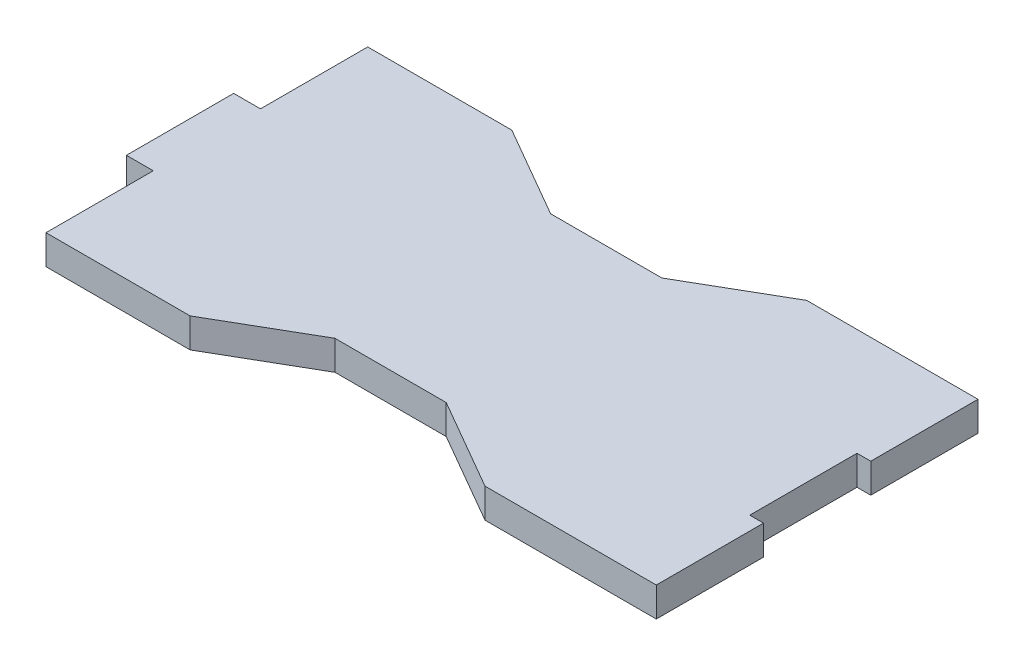
SolidWorks part; units mm, degrees
material "cardboard"
ref_plane "Front Plane" through (0, 0, 0) normal (0, 0, 1) x (1, 0, 0)
ref_plane "Top Plane" through (0, 0, 0) normal (0, 1, 0) x (1, 0, 0)
ref_plane "Right Plane" through (0, 0, 0) normal (1, 0, 0) x (0, 0, -1)
sketch "Sketch1" plane through (0, 0, 0) normal (0, 1, 0) x (1, 0, 0)
  line L0 (77.4818, 11.8659) -> (70.6317, 7.911)
  line L1 (102.9818, -12.1341) -> (109.832, -8.1792)
  line L2 (118.1317, 7.911) -> (109.832, 7.911)
  line L3 (118.1317, -8.1792) -> (109.832, -8.1792)
  line L4 (70.6317, 7.911) -> (62.332, 7.911)
  line L5 (124.9818, 11.8659) -> (118.1317, 7.911)
  line L6 (124.9818, -12.1341) -> (118.1317, -8.1792)
  line L7 (102.9818, 11.8659) -> (109.832, 7.911)
  line L8 (124.9818, 11.8659) -> (137.7318, 11.8659)
  line L9 (124.9818, -12.1341) -> (161.7318, -12.1341)
  line L10 (55.4818, 11.8659) -> (62.332, 7.911)
  line L11 (55.4818, -12.1341) -> (62.332, -8.1792)
  line L12 (77.4818, -12.1341) -> (70.6317, -8.1792)
  line L13 (70.6317, -8.1792) -> (62.332, -8.1792)
  line L14 (77.4818, 11.8659) -> (102.9818, 11.8659)
  line L15 (77.4818, -12.1341) -> (102.9818, -12.1341)
  line L16 (-12.2682, 77.6159) -> (-8.3133, 70.7658)
  line L17 (11.7318, 103.1159) -> (7.7769, 109.966)
  line L18 (-8.3133, 118.2658) -> (-8.3133, 109.966)
  line L19 (7.7769, 118.2658) -> (7.7769, 109.966)
  line L20 (-8.3133, 70.7658) -> (-8.3133, 62.466)
  line L21 (-12.2682, 125.1159) -> (-8.3133, 118.2658)
  line L22 (11.7318, 125.1159) -> (7.7769, 118.2658)
  line L23 (-12.2682, 103.1159) -> (-8.3133, 109.966)
  line L24 (-12.2682, 125.1159) -> (-12.2682, 137.8659)
  line L25 (11.7318, 125.1159) -> (11.7318, 161.8659)
  line L26 (-12.2682, 55.6159) -> (-8.3133, 62.466)
  line L27 (11.7318, 55.6159) -> (7.7769, 62.466)
  line L28 (11.7318, 77.6159) -> (7.7769, 70.7658)
  line L29 (7.7769, 70.7658) -> (7.7769, 62.466)
  line L30 (-12.2682, 77.6159) -> (-12.2682, 103.1159)
  line L31 (11.7318, 77.6159) -> (11.7318, 103.1159)
  line L32 (90.2318, 36.8659) -> (90.2318, 16.8659)
  line L33 (89.2318, 36.8659) -> (89.2318, 30.8659)
  line L34 (36.7318, 11.8659) -> (42.7318, 11.8659)
  line L35 (89.2318, 30.8659) -> (91.2318, 30.8659)
  line L36 (41.4818, 11.8659) -> (41.4818, 9.8659)
  line L37 (42.7318, 11.8659) -> (55.4818, 11.8659)
  line L38 (137.7318, 11.8659) -> (137.7318, -12.1341)
  line L39 (137.7318, 11.8659) -> (161.7318, 11.8659)
  line L40 (161.7318, 11.8659) -> (161.7318, 9.8659)
  line L41 (-28.7646, 14.2202) -> (-0.2682, -14.2762)
  line L42 (-28.7646, 14.2202) -> (-14.6225, 28.3623)
  line L43 (-0.2682, -14.2762) -> (13.8739, -0.1341)
  line L44 (-14.6225, 28.3623) -> (13.8739, -0.1341)
  line L45 (137.7318, 11.8659) -> (137.7318, 36.8659)
  line L46 (39.7318, 36.8659) -> (161.7318, 36.8659)
  line L47 (161.7318, 36.8659) -> (161.7318, 11.8659)
  line L48 (91.2318, 30.8659) -> (91.2318, 22.8659)
  line L49 (137.7318, 36.8659) -> (137.7318, 60.8659)
  line L50 (137.7318, 60.8659) -> (146.7318, 60.8659)
  line L51 (42.7318, 36.8659) -> (42.7318, 16.8659)
  line L52 (161.7318, 60.8659) -> (161.7318, 51.1879)
  line L53 (146.7318, 60.8659) -> (146.7318, 63.0659)
  line L54 (152.7318, 63.0659) -> (152.7318, 60.8659)
  line L55 (152.7318, 60.8659) -> (161.7318, 60.8659)
  line L56 (-59.2682, 137.8659) -> (-59.2682, 113.3659)
  line L57 (-39.2682, 113.3659) -> (-39.2682, 137.8659)
  line L58 (91.2318, 22.8659) -> (89.2318, 22.8659)
  line L59 (137.7318, -12.1341) -> (137.7318, -37.1341)
  line L60 (146.7318, -37.1341) -> (152.7318, -37.1341)
  line L61 (161.7318, -37.1341) -> (161.7318, -12.1341)
  line L62 (42.7318, -37.1341) -> (42.7318, -17.1341)
  line L63 (137.7318, -37.1341) -> (137.7318, -38.3141)
  line L64 (152.7318, -38.3141) -> (161.7318, -38.3141)
  line L65 (161.7318, -38.3141) -> (161.7318, -37.1341)
  line L66 (146.7318, -38.3141) -> (146.7318, -37.1341)
  line L67 (152.7318, -38.3141) -> (152.7318, -37.1341)
  line L68 (-38.4482, -138.1341) -> (-38.4482, -147.1341)
  line L69 (89.2318, 22.8659) -> (89.2318, 16.8659)
  line L70 (89.2318, 11.8659) -> (89.2318, 3.8659)
  line L71 (42.7318, -12.1341) -> (55.4818, -12.1341)
  line L72 (36.7318, -12.1341) -> (42.7318, -12.1341)
  line L73 (90.2056, 11.8659) -> (90.2056, -12.1341)
  line L74 (89.2318, 3.8659) -> (91.2318, 3.8659)
  line L75 (91.2318, 3.8659) -> (91.2318, -4.1341)
  line L76 (91.2318, -4.1341) -> (89.2318, -4.1341)
  line L77 (135.7318, 11.8659) -> (135.7318, 3.8659)
  line L78 (135.7318, 3.8659) -> (139.7318, 3.8659)
  line L79 (37.9118, 161.8659) -> (37.9118, 152.8659)
  line L80 (37.7318, 34.8659) -> (37.7318, 18.8659)
  line L81 (39.7318, 16.8659) -> (137.7318, 16.8659)
  line L82 (41.4818, 23.8659) -> (41.4818, 16.8659)
  line L83 (42.7318, 29.8659) -> (39.7318, 29.8659)
  line L84 (39.7318, 29.8659) -> (39.7318, 23.8659)
  line L85 (43.9818, 5.8659) -> (41.4818, 5.8659)
  line L86 (5.7318, -41.8841) -> (5.7318, -39.8841)
  line L87 (41.4818, -6.1341) -> (43.9818, -6.1341)
  line L88 (43.9818, 5.8659) -> (43.9818, -6.1341)
  line L89 (42.7318, 11.8659) -> (42.7318, 5.8659)
  line L90 (41.4818, 9.8659) -> (43.9818, 9.8659)
  line L91 (43.9818, 9.8659) -> (43.9818, 7.8659)
  line L92 (43.9818, 7.8659) -> (41.4818, 7.8659)
  line L93 (41.4818, 7.8659) -> (41.4818, 5.8659)
  line L94 (41.4818, -8.1341) -> (41.4818, -6.1341)
  line L95 (43.9818, -8.1341) -> (41.4818, -8.1341)
  line L96 (43.9818, -10.1341) -> (43.9818, -8.1341)
  line L97 (41.4818, -10.1341) -> (43.9818, -10.1341)
  line L98 (41.4818, -12.1341) -> (41.4818, -10.1341)
  line L99 (139.7318, 3.8659) -> (139.7318, -4.1341)
  line L100 (139.7318, -4.1341) -> (135.7318, -4.1341)
  line L101 (135.7318, -4.1341) -> (135.7318, -12.1341)
  line L102 (137.7318, 13.8659) -> (145.7318, 13.8659)
  line L103 (145.7318, 13.8659) -> (145.7318, 9.8659)
  line L104 (145.7318, 9.8659) -> (153.7318, 9.8659)
  line L105 (153.7318, 9.8659) -> (153.7318, 13.8659)
  line L106 (153.7318, 13.8659) -> (161.7318, 13.8659)
  line L107 (136.2318, 36.8659) -> (136.2318, 30.8659)
  line L108 (136.2318, 30.8659) -> (139.2318, 30.8659)
  line L109 (139.2318, 30.8659) -> (139.2318, 22.8659)
  line L110 (139.2318, 22.8659) -> (136.2318, 22.8659)
  line L111 (136.2318, 22.8659) -> (136.2318, 16.8659)
  line L112 (89.2318, -4.1341) -> (89.2318, -12.1341)
  line L113 (89.2318, -23.1341) -> (89.2318, -17.1341)
  line L114 (90.2318, -37.1341) -> (90.2318, -17.1341)
  line L115 (91.2318, -23.1341) -> (89.2318, -23.1341)
  line L116 (91.2318, -31.1341) -> (91.2318, -23.1341)
  line L117 (153.7318, -14.1341) -> (161.7318, -14.1341)
  line L118 (153.7318, -10.1341) -> (153.7318, -14.1341)
  line L119 (145.7318, -10.1341) -> (153.7318, -10.1341)
  line L120 (145.7318, -14.1341) -> (145.7318, -10.1341)
  line L121 (137.7318, -14.1341) -> (145.7318, -14.1341)
  line L122 (136.2318, -23.1341) -> (136.2318, -17.1341)
  line L123 (139.2318, -23.1341) -> (136.2318, -23.1341)
  line L124 (41.4818, 36.8659) -> (41.4818, 29.8659)
  line L125 (42.7318, 23.8659) -> (39.7318, 23.8659)
  line L126 (137.7318, -37.1341) -> (39.7318, -37.1341)
  line L127 (37.7318, -35.1341) -> (37.7318, -19.1341)
  line L128 (39.7318, -17.1341) -> (137.7318, -17.1341)
  line L129 (139.2318, -31.1341) -> (139.2318, -23.1341)
  line L130 (136.2318, -31.1341) -> (139.2318, -31.1341)
  line L131 (136.2318, -37.1341) -> (136.2318, -31.1341)
  line L132 (89.2318, -31.1341) -> (91.2318, -31.1341)
  line L133 (89.2318, -37.1341) -> (89.2318, -31.1341)
  line L134 (137.7318, 38.8659) -> (145.7318, 38.8659)
  line L135 (145.7318, 38.8659) -> (145.7318, 34.8659)
  line L136 (145.7318, 34.8659) -> (153.7318, 34.8659)
  line L137 (153.7318, 34.8659) -> (153.7318, 38.8659)
  line L138 (153.7318, 38.8659) -> (161.7318, 38.8659)
  line L139 (-44.7682, 133.6159) -> (-44.7682, 117.6159)
  line L140 (-56.2682, 133.6159) -> (-53.7682, 133.6159)
  line L141 (-56.2682, 133.6159) -> (-56.2682, 117.6159)
  line L142 (-56.2682, 117.6159) -> (-53.7682, 117.6159)
  line L143 (-53.7682, 133.6159) -> (-53.7682, 117.6159)
  line L144 (41.4818, -24.1341) -> (41.4818, -17.1341)
  line L145 (42.7318, -24.1341) -> (39.7318, -24.1341)
  line L146 (39.7318, -30.1341) -> (39.7318, -24.1341)
  line L147 (42.7318, -30.1341) -> (39.7318, -30.1341)
  line L148 (41.4818, -37.1341) -> (41.4818, -30.1341)
  line L149 (196.7318, 4.8659) -> (196.7318, -5.1341)
  line L150 (191.7318, 9.8659) -> (161.7318, 9.8659)
  line L151 (191.7318, -10.1341) -> (161.7318, -10.1341)
  line L152 (191.7318, 9.8659) -> (196.7318, 4.8659)
  line L153 (196.7318, -5.1341) -> (191.7318, -10.1341)
  line L154 (161.7318, -10.1341) -> (161.7318, -12.1341)
  line L155 (137.7318, 63.0659) -> (146.7318, 63.0659)
  line L156 (137.7318, 63.0659) -> (137.7318, 65.0659)
  line L157 (137.7318, 65.0659) -> (161.7318, 65.0659)
  line L158 (161.7318, 65.0659) -> (161.7318, 63.0659)
  line L159 (152.7318, 63.0659) -> (161.7318, 63.0659)
  line L160 (-42.2682, 117.6159) -> (-44.7682, 117.6159)
  line L161 (-42.2682, 133.6159) -> (-42.2682, 117.6159)
  line L162 (-42.2682, 133.6159) -> (-44.7682, 133.6159)
  line L163 (155.1318, 51.1879) -> (161.7318, 51.1879)
  line L164 (155.1318, 51.1879) -> (155.1318, 46.6879)
  line L165 (155.1318, 46.6879) -> (161.7318, 46.6879)
  line L166 (161.7318, 46.6879) -> (161.7318, 36.8659)
  line L167 (11.7318, -77.8841) -> (7.7769, -71.034)
  line L168 (-12.2682, -103.3841) -> (-8.3133, -110.2342)
  line L169 (7.7769, -118.534) -> (7.7769, -110.2342)
  line L170 (11.7318, -37.1341) -> (11.7318, -43.1341)
  line L171 (11.7318, -41.8841) -> (9.7318, -41.8841)
  line L172 (11.7318, -43.1341) -> (11.7318, -55.8841)
  line L173 (-8.3133, -118.534) -> (-8.3133, -110.2342)
  line L174 (7.7769, -71.034) -> (7.7769, -62.7342)
  line L175 (11.7318, -125.3841) -> (7.7769, -118.534)
  line L176 (-12.2682, -125.3841) -> (-8.3133, -118.534)
  line L177 (11.7318, -103.3841) -> (7.7769, -110.2342)
  line L178 (11.7318, -125.3841) -> (11.7318, -138.1341)
  line L179 (-12.2682, -125.3841) -> (-12.2682, -162.1341)
  line L180 (11.7318, -55.8841) -> (7.7769, -62.7342)
  line L181 (-12.2682, -55.8841) -> (-8.3133, -62.7342)
  line L182 (36.7318, -43.1341) -> (16.7318, -43.1341)
  line L183 (-12.2682, -77.8841) -> (-8.3133, -71.034)
  line L184 (-8.3133, -71.034) -> (-8.3133, -62.7342)
  line L185 (11.7318, -77.8841) -> (11.7318, -103.3841)
  line L186 (-12.2682, -77.8841) -> (-12.2682, -103.3841)
  line L187 (36.7318, -90.6341) -> (16.7318, -90.6341)
  line L188 (36.7318, -89.6341) -> (30.7318, -89.6341)
  line L189 (30.7318, -89.6341) -> (30.7318, -91.6341)
  line L190 (11.7318, -138.1341) -> (-12.2682, -138.1341)
  line L191 (11.7318, -138.1341) -> (11.7318, -162.1341)
  line L192 (11.7318, -162.1341) -> (9.7318, -162.1341)
  line L193 (11.7318, -138.1341) -> (36.7318, -138.1341)
  line L194 (36.7318, -40.1341) -> (36.7318, -162.1341)
  line L195 (-37.2682, -43.1341) -> (-17.2682, -43.1341)
  line L196 (36.7318, -162.1341) -> (11.7318, -162.1341)
  line L197 (30.7318, -91.6341) -> (22.7318, -91.6341)
  line L198 (36.7318, -138.1341) -> (60.7318, -138.1341)
  line L199 (60.7318, -138.1341) -> (60.7318, -147.1341)
  line L200 (60.7318, -162.1341) -> (51.0538, -162.1341)
  line L201 (60.7318, -147.1341) -> (62.9318, -147.1341)
  line L202 (62.9318, -153.1341) -> (60.7318, -153.1341)
  line L203 (60.7318, -153.1341) -> (60.7318, -162.1341)
  line L204 (-12.2682, -43.1341) -> (-12.2682, -55.8841)
  line L205 (-12.2682, -37.1341) -> (-12.2682, -43.1341)
  line L206 (22.7318, -91.6341) -> (22.7318, -89.6341)
  line L207 (-12.2682, -138.1341) -> (-37.2682, -138.1341)
  line L208 (-37.2682, -147.1341) -> (-37.2682, -153.1341)
  line L209 (37.9118, 146.8659) -> (37.9118, 137.8659)
  line L210 (34.7318, -38.1341) -> (18.7318, -38.1341)
  line L211 (16.7318, -40.1341) -> (16.7318, -138.1341)
  line L212 (23.7318, -41.8841) -> (16.7318, -41.8841)
  line L213 (29.7318, -43.1341) -> (29.7318, -40.1341)
  line L214 (29.7318, -40.1341) -> (23.7318, -40.1341)
  line L215 (5.7318, -44.3841) -> (5.7318, -41.8841)
  line L216 (-37.2682, -162.1341) -> (-12.2682, -162.1341)
  line L217 (-6.2682, -41.8841) -> (-6.2682, -44.3841)
  line L218 (5.7318, -44.3841) -> (-6.2682, -44.3841)
  line L219 (11.7318, -43.1341) -> (5.7318, -43.1341)
  line L220 (9.7318, -41.8841) -> (9.7318, -44.3841)
  line L221 (9.7318, -44.3841) -> (7.7318, -44.3841)
  line L222 (7.7318, -44.3841) -> (7.7318, -41.8841)
  line L223 (7.7318, -41.8841) -> (5.7318, -41.8841)
  line L224 (-8.2682, -41.8841) -> (-6.2682, -41.8841)
  line L225 (-8.2682, -44.3841) -> (-8.2682, -41.8841)
  line L226 (-10.2682, -44.3841) -> (-8.2682, -44.3841)
  line L227 (-10.2682, -41.8841) -> (-10.2682, -44.3841)
  line L228 (-12.2682, -41.8841) -> (-10.2682, -41.8841)
  line L229 (-37.2682, -138.1341) -> (-38.4482, -138.1341)
  line L230 (-38.4482, -153.1341) -> (-38.4482, -162.1341)
  line L231 (-38.4482, -162.1341) -> (-37.2682, -162.1341)
  line L232 (-38.4482, -147.1341) -> (-37.2682, -147.1341)
  line L233 (-38.4482, -153.1341) -> (-37.2682, -153.1341)
  line L234 (-162.2682, 38.0459) -> (-153.2682, 38.0459)
  line L235 (22.7318, -89.6341) -> (16.7318, -89.6341)
  line L236 (11.7318, -89.6341) -> (3.7318, -89.6341)
  line L237 (11.7318, -90.6079) -> (-12.2682, -90.6079)
  line L238 (3.7318, -89.6341) -> (3.7318, -91.6341)
  line L239 (3.7318, -91.6341) -> (-4.2682, -91.6341)
  line L240 (-4.2682, -91.6341) -> (-4.2682, -89.6341)
  line L241 (11.7318, -136.1341) -> (3.7318, -136.1341)
  line L242 (3.7318, -136.1341) -> (3.7318, -140.1341)
  line L243 (3.7318, -140.1341) -> (-4.2682, -140.1341)
  line L244 (-4.2682, -140.1341) -> (-4.2682, -136.1341)
  line L245 (-4.2682, -136.1341) -> (-12.2682, -136.1341)
  line L246 (13.7318, -138.1341) -> (13.7318, -146.1341)
  line L247 (13.7318, -146.1341) -> (9.7318, -146.1341)
  line L248 (9.7318, -146.1341) -> (9.7318, -154.1341)
  line L249 (9.7318, -154.1341) -> (13.7318, -154.1341)
  line L250 (13.7318, -154.1341) -> (13.7318, -162.1341)
  line L251 (36.7318, -136.6341) -> (30.7318, -136.6341)
  line L252 (30.7318, -136.6341) -> (30.7318, -139.6341)
  line L253 (30.7318, -139.6341) -> (22.7318, -139.6341)
  line L254 (36.7318, -41.8841) -> (29.7318, -41.8841)
  line L255 (23.7318, -43.1341) -> (23.7318, -40.1341)
  line L256 (-37.2682, -138.1341) -> (-37.2682, -40.1341)
  line L257 (-35.2682, -38.1341) -> (-19.2682, -38.1341)
  line L258 (-17.2682, -40.1341) -> (-17.2682, -138.1341)
  line L259 (22.7318, -139.6341) -> (22.7318, -136.6341)
  line L260 (22.7318, -136.6341) -> (16.7318, -136.6341)
  line L261 (-4.2682, -89.6341) -> (-12.2682, -89.6341)
  line L262 (-23.2682, -89.6341) -> (-17.2682, -89.6341)
  line L263 (-37.2682, -90.6341) -> (-17.2682, -90.6341)
  line L264 (-23.2682, -91.6341) -> (-23.2682, -89.6341)
  line L265 (-31.2682, -91.6341) -> (-23.2682, -91.6341)
  line L266 (-14.2682, -154.1341) -> (-14.2682, -162.1341)
  line L267 (-10.2682, -154.1341) -> (-14.2682, -154.1341)
  line L268 (-10.2682, -146.1341) -> (-10.2682, -154.1341)
  line L269 (-14.2682, -146.1341) -> (-10.2682, -146.1341)
  line L270 (-14.2682, -138.1341) -> (-14.2682, -146.1341)
  line L271 (-23.2682, -136.6341) -> (-17.2682, -136.6341)
  line L272 (-23.2682, -139.6341) -> (-23.2682, -136.6341)
  line L273 (-31.2682, -139.6341) -> (-23.2682, -139.6341)
  line L274 (-24.2682, -41.8841) -> (-17.2682, -41.8841)
  line L275 (-24.2682, -43.1341) -> (-24.2682, -40.1341)
  line L276 (-30.2682, -40.1341) -> (-24.2682, -40.1341)
  line L277 (-30.2682, -43.1341) -> (-30.2682, -40.1341)
  line L278 (-37.2682, -41.8841) -> (-30.2682, -41.8841)
  line L279 (-31.2682, -136.6341) -> (-31.2682, -139.6341)
  line L280 (-37.2682, -136.6341) -> (-31.2682, -136.6341)
  line L281 (-31.2682, -89.6341) -> (-31.2682, -91.6341)
  line L282 (-37.2682, -89.6341) -> (-31.2682, -89.6341)
  line L283 (38.7318, -138.1341) -> (38.7318, -146.1341)
  line L284 (38.7318, -146.1341) -> (34.7318, -146.1341)
  line L285 (34.7318, -146.1341) -> (34.7318, -154.1341)
  line L286 (34.7318, -154.1341) -> (38.7318, -154.1341)
  line L287 (38.7318, -154.1341) -> (38.7318, -162.1341)
  line L288 (4.7318, -197.1341) -> (-5.2682, -197.1341)
  line L289 (9.7318, -192.1341) -> (9.7318, -162.1341)
  line L290 (-10.2682, -192.1341) -> (-10.2682, -162.1341)
  line L291 (9.7318, -192.1341) -> (4.7318, -197.1341)
  line L292 (-5.2682, -197.1341) -> (-10.2682, -192.1341)
  line L293 (-10.2682, -162.1341) -> (-12.2682, -162.1341)
  line L294 (62.9318, -138.1341) -> (62.9318, -147.1341)
  line L295 (62.9318, -138.1341) -> (64.9318, -138.1341)
  line L296 (64.9318, -138.1341) -> (64.9318, -162.1341)
  line L297 (64.9318, -162.1341) -> (62.9318, -162.1341)
  line L298 (62.9318, -153.1341) -> (62.9318, -162.1341)
  line L299 (-37.2682, -12.1341) -> (-43.2682, -12.1341)
  line L300 (-42.0182, -12.1341) -> (-42.0182, -10.1341)
  line L301 (-43.2682, -12.1341) -> (-56.0182, -12.1341)
  line L302 (51.0538, -155.5341) -> (51.0538, -162.1341)
  line L303 (51.0538, -155.5341) -> (46.5538, -155.5341)
  line L304 (-43.2682, -37.1341) -> (-43.2682, -17.1341)
  line L305 (46.5538, -155.5341) -> (46.5538, -162.1341)
  line L306 (46.5538, -162.1341) -> (36.7318, -162.1341)
  line L307 (-78.0182, -12.1341) -> (-71.168, -8.1792)
  line L308 (-103.5182, 11.8659) -> (-110.3683, 7.911)
  line L309 (-118.668, -8.1792) -> (-110.3683, -8.1792)
  line L310 (-118.668, 7.911) -> (-110.3683, 7.911)
  line L311 (-71.168, -8.1792) -> (-62.8683, -8.1792)
  line L312 (-125.5182, -12.1341) -> (-118.668, -8.1792)
  line L313 (-125.5182, 11.8659) -> (-118.668, 7.911)
  line L314 (-103.5182, -12.1341) -> (-110.3683, -8.1792)
  line L315 (-125.5182, -12.1341) -> (-138.2682, -12.1341)
  line L316 (-43.2682, 36.8659) -> (-43.2682, 16.8659)
  line L317 (-125.5182, 11.8659) -> (-162.2682, 11.8659)
  line L318 (-56.0182, -12.1341) -> (-62.8683, -8.1792)
  line L319 (-56.0182, 11.8659) -> (-62.8683, 7.911)
  line L320 (-78.0182, 11.8659) -> (-71.168, 7.911)
  line L321 (-71.168, 7.911) -> (-62.8683, 7.911)
  line L322 (-78.0182, -12.1341) -> (-103.5182, -12.1341)
  line L323 (-78.0182, 11.8659) -> (-103.5182, 11.8659)
  line L324 (-90.7682, -37.1341) -> (-90.7682, -17.1341)
  line L325 (-43.2682, 11.8659) -> (-56.0182, 11.8659)
  line L326 (-37.2682, 11.8659) -> (-43.2682, 11.8659)
  line L327 (-89.7682, -37.1341) -> (-89.7682, -31.1341)
  line L328 (-89.7682, -31.1341) -> (-91.7682, -31.1341)
  line L329 (-138.2682, -12.1341) -> (-138.2682, 11.8659)
  line L330 (-138.2682, -12.1341) -> (-162.2682, -12.1341)
  line L331 (-162.2682, -12.1341) -> (-162.2682, -10.1341)
  line L332 (-138.2682, -12.1341) -> (-138.2682, -37.1341)
  line L333 (137.7318, -38.3141) -> (146.7318, -38.3141)
  line L334 (-38.2682, -35.1341) -> (-38.2682, -19.1341)
  line L335 (-40.2682, -17.1341) -> (-138.2682, -17.1341)
  line L336 (-42.0182, -24.1341) -> (-42.0182, -17.1341)
  line L337 (-43.2682, -30.1341) -> (-40.2682, -30.1341)
  line L338 (-40.2682, -30.1341) -> (-40.2682, -24.1341)
  line L339 (-44.5182, -6.1341) -> (-42.0182, -6.1341)
  line L340 (-40.2682, -37.1341) -> (-162.2682, -37.1341)
  line L341 (-42.0182, 5.8659) -> (-44.5182, 5.8659)
  line L342 (-44.5182, -6.1341) -> (-44.5182, 5.8659)
  line L343 (-43.2682, -12.1341) -> (-43.2682, -6.1341)
  line L344 (-42.0182, -10.1341) -> (-44.5182, -10.1341)
  line L345 (-44.5182, -10.1341) -> (-44.5182, -8.1341)
  line L346 (-44.5182, -8.1341) -> (-42.0182, -8.1341)
  line L347 (-42.0182, -8.1341) -> (-42.0182, -6.1341)
  line L348 (-42.0182, 7.8659) -> (-42.0182, 5.8659)
  line L349 (-44.5182, 7.8659) -> (-42.0182, 7.8659)
  line L350 (-44.5182, 9.8659) -> (-44.5182, 7.8659)
  line L351 (-42.0182, 9.8659) -> (-44.5182, 9.8659)
  line L352 (-42.0182, 11.8659) -> (-42.0182, 9.8659)
  line L353 (-162.2682, -37.1341) -> (-162.2682, -12.1341)
  line L354 (-91.7682, -31.1341) -> (-91.7682, -23.1341)
  line L355 (-138.2682, -37.1341) -> (-138.2682, -61.1341)
  line L356 (-138.2682, -61.1341) -> (-147.2682, -61.1341)
  line L357 (-162.2682, -61.1341) -> (-162.2682, -51.4561)
  line L358 (-147.2682, -61.1341) -> (-147.2682, -63.3341)
  line L359 (-153.2682, -63.3341) -> (-153.2682, -61.1341)
  line L360 (-153.2682, -61.1341) -> (-162.2682, -61.1341)
  line L361 (-91.7682, -23.1341) -> (-89.7682, -23.1341)
  line L362 (-138.2682, 11.8659) -> (-138.2682, 36.8659)
  line L363 (-147.2682, 36.8659) -> (-153.2682, 36.8659)
  line L364 (-162.2682, 36.8659) -> (-162.2682, 11.8659)
  line L365 (-138.2682, 36.8659) -> (-138.2682, 38.0459)
  line L366 (-162.2682, 38.0459) -> (-162.2682, 36.8659)
  line L367 (-147.2682, 38.0459) -> (-147.2682, 36.8659)
  line L368 (-153.2682, 38.0459) -> (-153.2682, 36.8659)
  line L369 (-147.2682, 38.0459) -> (-138.2682, 38.0459)
  line L370 (-89.7682, -23.1341) -> (-89.7682, -17.1341)
  line L371 (-89.7682, -12.1341) -> (-89.7682, -4.1341)
  line L372 (-90.742, -12.1341) -> (-90.742, 11.8659)
  line L373 (-89.7682, -4.1341) -> (-91.7682, -4.1341)
  line L374 (-42.0182, -37.1341) -> (-42.0182, -30.1341)
  line L375 (-43.2682, -24.1341) -> (-40.2682, -24.1341)
  line L376 (-138.2682, 36.8659) -> (-40.2682, 36.8659)
  line L377 (-38.2682, 34.8659) -> (-38.2682, 18.8659)
  line L378 (-40.2682, 16.8659) -> (-138.2682, 16.8659)
  line L379 (-91.7682, -4.1341) -> (-91.7682, 3.8659)
  line L380 (-91.7682, 3.8659) -> (-89.7682, 3.8659)
  line L381 (-136.2682, -12.1341) -> (-136.2682, -4.1341)
  line L382 (-136.2682, -4.1341) -> (-140.2682, -4.1341)
  line L383 (-140.2682, -4.1341) -> (-140.2682, 3.8659)
  line L384 (-140.2682, 3.8659) -> (-136.2682, 3.8659)
  line L385 (-136.2682, 3.8659) -> (-136.2682, 11.8659)
  line L386 (-138.2682, -14.1341) -> (-146.2682, -14.1341)
  line L387 (-146.2682, -14.1341) -> (-146.2682, -10.1341)
  line L388 (-146.2682, -10.1341) -> (-154.2682, -10.1341)
  line L389 (-154.2682, -10.1341) -> (-154.2682, -14.1341)
  line L390 (-154.2682, -14.1341) -> (-162.2682, -14.1341)
  line L391 (-136.7682, -37.1341) -> (-136.7682, -31.1341)
  line L392 (-37.2682, 90.3659) -> (-17.2682, 90.3659)
  line L393 (-37.2682, 89.3659) -> (-31.2682, 89.3659)
  line L394 (-42.0182, 23.8659) -> (-42.0182, 16.8659)
  line L395 (-43.2682, 23.8659) -> (-40.2682, 23.8659)
  line L396 (-40.2682, 29.8659) -> (-40.2682, 23.8659)
  line L397 (-43.2682, 29.8659) -> (-40.2682, 29.8659)
  line L398 (-42.0182, 36.8659) -> (-42.0182, 29.8659)
  line L399 (-136.7682, -31.1341) -> (-139.7682, -31.1341)
  line L400 (-139.7682, -31.1341) -> (-139.7682, -23.1341)
  line L401 (-139.7682, -23.1341) -> (-136.7682, -23.1341)
  line L402 (-136.7682, -23.1341) -> (-136.7682, -17.1341)
  line L403 (-89.7682, 3.8659) -> (-89.7682, 11.8659)
  line L404 (-89.7682, 22.8659) -> (-89.7682, 16.8659)
  line L405 (-90.7682, 36.8659) -> (-90.7682, 16.8659)
  line L406 (-91.7682, 22.8659) -> (-89.7682, 22.8659)
  line L407 (-91.7682, 30.8659) -> (-91.7682, 22.8659)
  line L408 (-154.2682, 13.8659) -> (-162.2682, 13.8659)
  line L409 (-154.2682, 9.8659) -> (-154.2682, 13.8659)
  line L410 (-146.2682, 9.8659) -> (-154.2682, 9.8659)
  line L411 (-146.2682, 13.8659) -> (-146.2682, 9.8659)
  line L412 (-138.2682, 13.8659) -> (-146.2682, 13.8659)
  line L413 (-136.7682, 22.8659) -> (-136.7682, 16.8659)
  line L414 (-139.7682, 22.8659) -> (-136.7682, 22.8659)
  line L415 (-139.7682, 30.8659) -> (-139.7682, 22.8659)
  line L416 (-136.7682, 30.8659) -> (-139.7682, 30.8659)
  line L417 (-136.7682, 36.8659) -> (-136.7682, 30.8659)
  line L418 (-89.7682, 30.8659) -> (-91.7682, 30.8659)
  line L419 (-89.7682, 36.8659) -> (-89.7682, 30.8659)
  line L420 (-138.2682, -39.1341) -> (-146.2682, -39.1341)
  line L421 (-146.2682, -39.1341) -> (-146.2682, -35.1341)
  line L422 (-146.2682, -35.1341) -> (-154.2682, -35.1341)
  line L423 (-154.2682, -35.1341) -> (-154.2682, -39.1341)
  line L424 (-154.2682, -39.1341) -> (-162.2682, -39.1341)
  line L425 (-12.2682, 41.6159) -> (-10.2682, 41.6159)
  line L426 (-31.2682, 89.3659) -> (-31.2682, 91.3659)
  line L427 (-12.2682, 137.8659) -> (11.7318, 137.8659)
  line L428 (-12.2682, 137.8659) -> (-12.2682, 161.8659)
  line L429 (-12.2682, 161.8659) -> (-10.2682, 161.8659)
  line L430 (-12.2682, 137.8659) -> (-37.2682, 137.8659)
  line L431 (-37.2682, 137.8659) -> (-37.2682, 161.8659)
  line L432 (-37.2682, 161.8659) -> (-12.2682, 161.8659)
  line L433 (-37.2682, 137.8659) -> (-37.2682, 42.8659)
  line L434 (-37.2682, 42.8659) -> (-17.2682, 42.8659)
  line L435 (-17.2682, 42.8659) -> (-17.2682, 137.8659)
  line L436 (-31.2682, 91.3659) -> (-23.2682, 91.3659)
  line L437 (-37.2682, 137.8659) -> (-61.2682, 137.8659)
  line L438 (-61.2682, 137.8659) -> (-61.2682, 146.8659)
  line L439 (-61.2682, 161.8659) -> (-51.5902, 161.8659)
  line L440 (-61.2682, 146.8659) -> (-63.4682, 146.8659)
  line L441 (-63.4682, 152.8659) -> (-61.2682, 152.8659)
  line L442 (-61.2682, 152.8659) -> (-61.2682, 161.8659)
  line L443 (-59.2682, 113.3659) -> (-39.2682, 113.3659)
  line L444 (36.7318, 42.8659) -> (16.7318, 42.8659)
  line L445 (-23.2682, 91.3659) -> (-23.2682, 89.3659)
  line L446 (36.7318, 137.8659) -> (36.7318, 42.8659)
  line L447 (16.7318, 42.8659) -> (16.7318, 137.8659)
  line L448 (11.7318, 137.8659) -> (36.7318, 137.8659)
  line L449 (36.7318, 146.8659) -> (36.7318, 152.8659)
  line L450 (36.7318, 161.8659) -> (11.7318, 161.8659)
  line L451 (11.7318, 36.8659) -> (11.7318, 55.6159)
  line L452 (36.7318, 137.8659) -> (37.9118, 137.8659)
  line L453 (37.9118, 161.8659) -> (36.7318, 161.8659)
  line L454 (37.9118, 146.8659) -> (36.7318, 146.8659)
  line L455 (37.9118, 152.8659) -> (36.7318, 152.8659)
  line L456 (-37.2682, 42.8659) -> (-37.2682, 39.8659)
  line L457 (-35.2682, 37.8659) -> (-19.2682, 37.8659)
  line L458 (-17.2682, 39.8659) -> (-17.2682, 42.8659)
  line L459 (34.7318, 37.8659) -> (18.7318, 37.8659)
  line L460 (16.7318, 39.8659) -> (16.7318, 42.8659)
  line L461 (-6.2682, 44.1159) -> (-6.2682, 41.6159)
  line L462 (-23.2682, 89.3659) -> (-17.2682, 89.3659)
  line L463 (5.7318, 41.6159) -> (5.7318, 44.1159)
  line L464 (-6.2682, 44.1159) -> (5.7318, 44.1159)
  line L465 (-12.2682, 42.8659) -> (-6.2682, 42.8659)
  line L466 (-10.2682, 41.6159) -> (-10.2682, 44.1159)
  line L467 (-10.2682, 44.1159) -> (-8.2682, 44.1159)
  line L468 (-8.2682, 44.1159) -> (-8.2682, 41.6159)
  line L469 (-8.2682, 41.6159) -> (-6.2682, 41.6159)
  line L470 (7.7318, 41.6159) -> (5.7318, 41.6159)
  line L471 (7.7318, 44.1159) -> (7.7318, 41.6159)
  line L472 (9.7318, 44.1159) -> (7.7318, 44.1159)
  line L473 (9.7318, 41.6159) -> (9.7318, 44.1159)
  line L474 (11.7318, 41.6159) -> (9.7318, 41.6159)
  line L475 (-12.2682, 89.3659) -> (-4.2682, 89.3659)
  line L476 (-12.2682, 90.3397) -> (11.7318, 90.3397)
  line L477 (-4.2682, 89.3659) -> (-4.2682, 91.3659)
  line L478 (-4.2682, 91.3659) -> (3.7318, 91.3659)
  line L479 (3.7318, 91.3659) -> (3.7318, 89.3659)
  line L480 (-12.2682, 135.8659) -> (-4.2682, 135.8659)
  line L481 (-4.2682, 135.8659) -> (-4.2682, 139.8659)
  line L482 (-4.2682, 139.8659) -> (3.7318, 139.8659)
  line L483 (3.7318, 139.8659) -> (3.7318, 135.8659)
  line L484 (3.7318, 135.8659) -> (11.7318, 135.8659)
  line L485 (-14.2682, 137.8659) -> (-14.2682, 145.8659)
  line L486 (-14.2682, 145.8659) -> (-10.2682, 145.8659)
  line L487 (-10.2682, 145.8659) -> (-10.2682, 153.8659)
  line L488 (-10.2682, 153.8659) -> (-14.2682, 153.8659)
  line L489 (-14.2682, 153.8659) -> (-14.2682, 161.8659)
  line L490 (-37.2682, 136.3659) -> (-31.2682, 136.3659)
  line L491 (-31.2682, 136.3659) -> (-31.2682, 139.3659)
  line L492 (-31.2682, 139.3659) -> (-23.2682, 139.3659)
  line L493 (-23.2682, 139.3659) -> (-23.2682, 136.3659)
  line L494 (-23.2682, 136.3659) -> (-17.2682, 136.3659)
  line L495 (3.7318, 89.3659) -> (11.7318, 89.3659)
  line L496 (22.7318, 89.3659) -> (16.7318, 89.3659)
  line L497 (36.7318, 90.3659) -> (16.7318, 90.3659)
  line L498 (22.7318, 91.3659) -> (22.7318, 89.3659)
  line L499 (30.7318, 91.3659) -> (22.7318, 91.3659)
  line L500 (-37.2682, 41.6159) -> (-30.2682, 41.6159)
  line L501 (29.7318, 39.8659) -> (23.7318, 39.8659)
  line L502 (23.7318, 41.6159) -> (16.7318, 41.6159)
  line L503 (-30.2682, 42.8659) -> (-30.2682, 39.8659)
  line L504 (-24.2682, 41.6159) -> (-17.2682, 41.6159)
  line L505 (13.7318, 153.8659) -> (13.7318, 161.8659)
  line L506 (9.7318, 153.8659) -> (13.7318, 153.8659)
  line L507 (9.7318, 145.8659) -> (9.7318, 153.8659)
  line L508 (13.7318, 145.8659) -> (9.7318, 145.8659)
  line L509 (13.7318, 137.8659) -> (13.7318, 145.8659)
  line L510 (22.7318, 136.3659) -> (16.7318, 136.3659)
  line L511 (22.7318, 139.3659) -> (22.7318, 136.3659)
  line L512 (30.7318, 139.3659) -> (22.7318, 139.3659)
  line L513 (30.7318, 136.3659) -> (30.7318, 139.3659)
  line L514 (36.7318, 136.3659) -> (30.7318, 136.3659)
  line L515 (30.7318, 89.3659) -> (30.7318, 91.3659)
  line L516 (36.7318, 89.3659) -> (30.7318, 89.3659)
  line L517 (11.7318, 36.8659) -> (20.6963, 27.9014)
  line L518 (36.7318, -12.1341) -> (27.7673, -21.0986)
  line L519 (-12.2682, -37.1341) -> (-21.2327, -28.1696)
  line L520 (23.7318, 42.8659) -> (23.7318, 39.8659)
  line L521 (-24.2682, 42.8659) -> (-24.2682, 39.8659)
  line L522 (29.7318, 42.8659) -> (29.7318, 39.8659)
  line L523 (36.7318, 41.6159) -> (29.7318, 41.6159)
  line L524 (-39.2682, 137.8659) -> (-39.2682, 145.8659)
  line L525 (-39.2682, 145.8659) -> (-35.2682, 145.8659)
  line L526 (-35.2682, 145.8659) -> (-35.2682, 153.8659)
  line L527 (-35.2682, 153.8659) -> (-39.2682, 153.8659)
  line L528 (-39.2682, 153.8659) -> (-39.2682, 161.8659)
  line L529 (-59.2682, 136.3659) -> (-52.2682, 136.3659)
  line L530 (-52.2682, 136.3659) -> (-52.2682, 139.3659)
  line L531 (-52.2682, 139.3659) -> (-46.2682, 139.3659)
  line L532 (-46.2682, 139.3659) -> (-46.2682, 136.3659)
  line L533 (-46.2682, 136.3659) -> (-39.2682, 136.3659)
  line L534 (-12.2682, 36.8659) -> (-12.2682, 55.6159)
  line L535 (42.7318, -6.1341) -> (42.7318, -12.1341)
  line L536 (5.7318, 42.8659) -> (11.7318, 42.8659)
  line L537 (-43.2682, 5.8659) -> (-43.2682, 11.8659)
  line L538 (-6.2682, -43.1341) -> (-12.2682, -43.1341)
  line L539 (-5.2682, 196.8659) -> (4.7318, 196.8659)
  line L540 (-10.2682, 191.8659) -> (-10.2682, 161.8659)
  line L541 (9.7318, 191.8659) -> (9.7318, 161.8659)
  line L542 (-10.2682, 191.8659) -> (-5.2682, 196.8659)
  line L543 (4.7318, 196.8659) -> (9.7318, 191.8659)
  line L544 (133.4818, 55.8659) -> (117.4818, 55.8659)
  line L545 (133.4818, 55.8659) -> (133.4818, 53.3659)
  line L546 (-197.2682, -5.1341) -> (-197.2682, 4.8659)
  line L547 (-192.2682, -10.1341) -> (-162.2682, -10.1341)
  line L548 (-192.2682, 9.8659) -> (-162.2682, 9.8659)
  line L549 (-192.2682, -10.1341) -> (-197.2682, -5.1341)
  line L550 (-197.2682, 4.8659) -> (-192.2682, 9.8659)
  line L551 (-162.2682, 9.8659) -> (-162.2682, 11.8659)
  line L552 (-138.2682, -63.3341) -> (-147.2682, -63.3341)
  line L553 (-138.2682, -63.3341) -> (-138.2682, -65.3341)
  line L554 (-138.2682, -65.3341) -> (-162.2682, -65.3341)
  line L555 (-162.2682, -65.3341) -> (-162.2682, -63.3341)
  line L556 (9.7318, 161.8659) -> (11.7318, 161.8659)
  line L557 (-153.2682, -63.3341) -> (-162.2682, -63.3341)
  line L558 (133.4818, 53.3659) -> (117.4818, 53.3659)
  line L559 (117.4818, 55.8659) -> (117.4818, 53.3659)
  line L560 (133.4818, 44.3659) -> (117.4818, 44.3659)
  line L561 (133.4818, 41.8659) -> (133.4818, 44.3659)
  line L562 (133.4818, 41.8659) -> (117.4818, 41.8659)
  line L563 (117.4818, 41.8659) -> (117.4818, 44.3659)
  line L564 (136.2318, 58.8659) -> (136.2318, 51.8659)
  line L565 (136.2318, 51.8659) -> (139.2318, 51.8659)
  line L566 (-155.6682, -51.4561) -> (-162.2682, -51.4561)
  line L567 (-155.6682, -51.4561) -> (-155.6682, -46.9561)
  line L568 (-155.6682, -46.9561) -> (-162.2682, -46.9561)
  line L569 (-63.4682, 137.8659) -> (-63.4682, 146.8659)
  line L570 (-63.4682, 137.8659) -> (-65.4682, 137.8659)
  line L571 (-65.4682, 137.8659) -> (-65.4682, 161.8659)
  line L572 (-65.4682, 161.8659) -> (-63.4682, 161.8659)
  line L573 (-63.4682, 152.8659) -> (-63.4682, 161.8659)
  line L574 (-162.2682, -46.9561) -> (-162.2682, -37.1341)
  line L575 (139.2318, 51.8659) -> (139.2318, 45.8659)
  line L576 (-46.6303, 123.7107) -> (-47.7682, 123.7107)
  line L577 (-51.9061, 127.752) -> (-50.7682, 127.752)
  line L578 (-51.9061, 127.752) -> (-51.9061, 123.7107)
  line L579 (-51.9061, 123.7107) -> (-50.7682, 123.7107)
  line L580 (-50.7682, 127.752) -> (-50.7682, 123.7107)
  line L581 (-47.7682, 127.752) -> (-47.7682, 123.7107)
  line L582 (-46.6303, 127.752) -> (-47.7682, 127.752)
  line L583 (-46.6303, 127.752) -> (-46.6303, 123.7107)
  line L584 (139.2318, 45.8659) -> (136.2318, 45.8659)
  line L585 (136.2318, 45.8659) -> (136.2318, 38.8659)
  line L586 (113.2318, 38.8659) -> (137.7318, 38.8659)
  line L587 (113.2318, 58.8659) -> (113.2318, 38.8659)
  line L588 (137.7318, 58.8659) -> (113.2318, 58.8659)
  line L589 (55.7318, -133.8841) -> (55.7318, -117.8841)
  line L590 (55.7318, -133.8841) -> (53.2318, -133.8841)
  line L591 (-51.5902, 155.2659) -> (-51.5902, 161.8659)
  line L592 (-51.5902, 155.2659) -> (-47.0902, 155.2659)
  line L593 (-47.0902, 155.2659) -> (-47.0902, 161.8659)
  line L594 (-47.0902, 161.8659) -> (-37.2682, 161.8659)
  line L595 (53.2318, -133.8841) -> (53.2318, -117.8841)
  line L596 (55.7318, -117.8841) -> (53.2318, -117.8841)
  line L597 (-14.1616, 34.9725) -> (-12.2682, 36.8659)
  line L598 (-21.2327, 34.9725) -> (-23.354, 37.0938)
  line L599 (-35.3748, 20.8304) -> (-37.4961, 22.9517)
  line L600 (-37.4961, 22.9517) -> (-23.354, 37.0938)
  line L601 (5.7318, -39.8841) -> (-6.2682, -39.8841)
  line L602 (41.4818, 5.8659) -> (39.4818, 5.8659)
  line L603 (-6.2682, -41.8841) -> (-6.2682, -39.8841)
  line L604 (41.4818, -6.1341) -> (39.4818, -6.1341)
  line L605 (39.4818, 5.8659) -> (39.4818, -6.1341)
  line L606 (-42.0182, -6.1341) -> (-40.0182, -6.1341)
  line L607 (-40.0182, -6.1341) -> (-40.0182, 5.8659)
  line L608 (-42.0182, 5.8659) -> (-40.0182, 5.8659)
  line L609 (-6.2682, 41.6159) -> (-6.2682, 39.6159)
  line L610 (-6.2682, 39.6159) -> (5.7318, 39.6159)
  line L611 (5.7318, 41.6159) -> (5.7318, 39.6159)
  line L612 (-37.2682, 11.8659) -> (-35.3748, 13.7593)
  line L613 (-30.2682, 39.8659) -> (-24.2682, 39.8659)
  line L614 (25.646, -18.9772) -> (18.575, -26.0483)
  line L615 (18.575, 25.7801) -> (25.646, 18.709)
  line L616 (25.646, 18.709) -> (27.7673, 20.8304)
  line L617 (44.2318, -133.8841) -> (44.2318, -117.8841)
  line L618 (41.7318, -133.8841) -> (44.2318, -133.8841)
  line L619 (41.7318, -133.8841) -> (41.7318, -117.8841)
  line L620 (41.7318, -117.8841) -> (44.2318, -117.8841)
  line L621 (58.7318, -136.6341) -> (51.7318, -136.6341)
  line L622 (51.7318, -136.6341) -> (51.7318, -139.6341)
  line L623 (51.7318, -139.6341) -> (45.7318, -139.6341)
  line L624 (45.7318, -139.6341) -> (45.7318, -136.6341)
  line L625 (45.7318, -136.6341) -> (38.7318, -136.6341)
  line L626 (38.7318, -113.6341) -> (38.7318, -138.1341)
  line L627 (58.7318, -113.6341) -> (38.7318, -113.6341)
  line L628 (58.7318, -138.1341) -> (58.7318, -113.6341)
  line L629 (-134.0182, -56.1341) -> (-118.0182, -56.1341)
  line L630 (-134.0182, -56.1341) -> (-134.0182, -53.6341)
  line L631 (-134.0182, -53.6341) -> (-118.0182, -53.6341)
  line L632 (-118.0182, -56.1341) -> (-118.0182, -53.6341)
  line L633 (-134.0182, -44.6341) -> (-118.0182, -44.6341)
  line L634 (-134.0182, -42.1341) -> (-134.0182, -44.6341)
  line L635 (-134.0182, -42.1341) -> (-118.0182, -42.1341)
  line L636 (-118.0182, -42.1341) -> (-118.0182, -44.6341)
  line L637 (-136.7682, -59.1341) -> (-136.7682, -52.1341)
  line L638 (-136.7682, -52.1341) -> (-139.7682, -52.1341)
  line L639 (-139.7682, -52.1341) -> (-139.7682, -46.1341)
  line L640 (-139.7682, -46.1341) -> (-136.7682, -46.1341)
  line L641 (-136.7682, -46.1341) -> (-136.7682, -39.1341)
  line L642 (-113.7682, -39.1341) -> (-138.2682, -39.1341)
  line L643 (-113.7682, -59.1341) -> (-113.7682, -39.1341)
  line L644 (-138.2682, -59.1341) -> (-113.7682, -59.1341)
  line L645 (127.6179, 51.5038) -> (123.5766, 51.5038)
  line L646 (127.6179, 51.5038) -> (127.6179, 50.3659)
  line L647 (127.6179, 50.3659) -> (123.5766, 50.3659)
  line L648 (123.5766, 51.5038) -> (123.5766, 50.3659)
  line L649 (127.6179, 47.3659) -> (123.5766, 47.3659)
  line L650 (18.575, 25.7801) -> (20.6963, 27.9014)
  line L651 (127.6179, 46.228) -> (127.6179, 47.3659)
  line L652 (127.6179, 46.228) -> (123.5766, 46.228)
  line L653 (123.5766, 46.228) -> (123.5766, 47.3659)
  line L654 (51.3697, -128.0202) -> (51.3697, -123.9789)
  line L655 (51.3697, -128.0202) -> (50.2318, -128.0202)
  line L656 (50.2318, -128.0202) -> (50.2318, -123.9789)
  line L657 (51.3697, -123.9789) -> (50.2318, -123.9789)
  line L658 (47.2318, -128.0202) -> (47.2318, -123.9789)
  line L659 (46.0939, -128.0202) -> (47.2318, -128.0202)
  line L660 (46.0939, -128.0202) -> (46.0939, -123.9789)
  line L661 (46.0939, -123.9789) -> (47.2318, -123.9789)
  line L662 (-128.1543, -51.772) -> (-124.113, -51.772)
  line L663 (-128.1543, -51.772) -> (-128.1543, -50.6341)
  line L664 (-128.1543, -50.6341) -> (-124.113, -50.6341)
  line L665 (-124.113, -51.772) -> (-124.113, -50.6341)
  line L666 (-128.1543, -47.6341) -> (-124.113, -47.6341)
  line L667 (-128.1543, -46.4962) -> (-128.1543, -47.6341)
  line L668 (-128.1543, -46.4962) -> (-124.113, -46.4962)
  line L669 (-124.113, -46.4962) -> (-124.113, -47.6341)
  line L670 (27.7673, 20.8304) -> (36.7318, 11.8659)
  line L671 (18.575, -26.0483) -> (20.6963, -28.1696)
  line L672 (25.646, -18.9772) -> (27.7673, -21.0986)
  line L673 (-19.1113, -26.0483) -> (-26.1824, -18.9772)
  line L674 (-26.1824, -18.9772) -> (-28.3037, -21.0986)
  line L675 (-19.1113, -26.0483) -> (-21.2327, -28.1696)
  line L676 (20.6963, -28.1696) -> (11.7318, -37.1341)
  line L677 (-28.3037, -21.0986) -> (-37.2682, -12.1341)
  line L678 (36.7318, 42.8659) -> (36.7318, 39.8659)
  circle A0 centre (156.4493, 42.1484) radius 1.5
  circle A1 centre (143.0143, 55.5834) radius 1.5
  circle A2 centre (155.3887, 54.5228) radius 1.5
  circle A3 centre (144.075, 43.209) radius 1.5
  circle A4 centre (149.7318, 48.8659) radius 3.1
  circle A5 centre (149.7318, 24.3659) radius 5
  circle A6 centre (149.7318, -24.6341) radius 5
  circle A7 centre (66.4818, 26.8659) radius 5
  circle A8 centre (113.7324, 26.8659) radius 5
  circle A9 centre (66.4818, -27.1341) radius 5
  circle A10 centre (113.7324, -27.1341) radius 5
  circle A11 centre (149.7318, -0.1341) radius 7
  circle A12 centre (42.0143, -156.8516) radius 1.5
  circle A13 centre (55.4493, -143.4166) radius 1.5
  circle A14 centre (54.3887, -155.791) radius 1.5
  circle A15 centre (43.075, -144.4772) radius 1.5
  circle A16 centre (48.7318, -150.1341) radius 3.1
  circle A17 centre (24.2318, -150.1341) radius 5
  circle A18 centre (-42.5507, 156.5834) radius 1.5
  circle A19 centre (-55.9857, 143.1484) radius 1.5
  circle A20 centre (-54.925, 155.5228) radius 1.5
  circle A21 centre (-43.6113, 144.209) radius 1.5
  circle A22 centre (-49.2682, 149.8659) radius 3.1
  circle A23 centre (-24.7682, -150.1341) radius 5
  circle A24 centre (26.7318, -66.8841) radius 5
  circle A25 centre (26.7318, -114.1347) radius 5
  circle A26 centre (-27.2682, -66.8841) radius 5
  circle A27 centre (-27.2682, -114.1347) radius 5
  circle A28 centre (-0.2682, -150.1341) radius 7
  circle A29 centre (-156.9857, -42.4166) radius 1.5
  circle A30 centre (-24.7682, 149.8659) radius 5
  circle A31 centre (24.2318, 149.8659) radius 5
  circle A32 centre (-143.5507, -55.8516) radius 1.5
  circle A33 centre (-155.925, -54.791) radius 1.5
  circle A34 centre (-144.6113, -43.4772) radius 1.5
  circle A35 centre (-150.2682, -49.1341) radius 3.1
  circle A36 centre (-150.2682, -24.6341) radius 5
  circle A37 centre (-150.2682, 24.3659) radius 5
  circle A38 centre (-67.0182, -27.1341) radius 5
  circle A39 centre (-114.2688, -27.1341) radius 5
  circle A40 centre (-67.0182, 26.8659) radius 5
  circle A41 centre (-114.2688, 26.8659) radius 5
  circle A42 centre (-150.2682, -0.1341) radius 7
  circle A43 centre (-27.2682, 66.6159) radius 5
  circle A44 centre (-27.2682, 113.8665) radius 5
  circle A45 centre (26.7318, 66.6159) radius 5
  circle A46 centre (26.7318, 113.8665) radius 5
  arc A47 (39.7318, 36.8659) -> (37.7318, 34.8659) centre (39.7318, 34.8659) ccw
  arc A48 (37.7318, 18.8659) -> (39.7318, 16.8659) centre (39.7318, 18.8659) ccw
  arc A49 (-19.2682, 37.8659) -> (-17.2682, 39.8659) centre (-19.2682, 39.8659) ccw
  arc A50 (-37.2682, 39.8659) -> (-35.2682, 37.8659) centre (-35.2682, 39.8659) ccw
  arc A51 (36.7318, 39.8659) -> (34.7318, 37.8659) centre (34.7318, 39.8659) cw
  arc A52 (18.7318, 37.8659) -> (16.7318, 39.8659) centre (18.7318, 39.8659) cw
  arc A53 (39.7318, -37.1341) -> (37.7318, -35.1341) centre (39.7318, -35.1341) cw
  arc A54 (37.7318, -19.1341) -> (39.7318, -17.1341) centre (39.7318, -19.1341) cw
  arc A55 (36.7318, -40.1341) -> (34.7318, -38.1341) centre (34.7318, -40.1341) ccw
  arc A56 (18.7318, -38.1341) -> (16.7318, -40.1341) centre (18.7318, -40.1341) ccw
  arc A57 (-37.2682, -40.1341) -> (-35.2682, -38.1341) centre (-35.2682, -40.1341) cw
  arc A58 (-19.2682, -38.1341) -> (-17.2682, -40.1341) centre (-19.2682, -40.1341) cw
  arc A59 (-40.2682, -37.1341) -> (-38.2682, -35.1341) centre (-40.2682, -35.1341) ccw
  arc A60 (-38.2682, -19.1341) -> (-40.2682, -17.1341) centre (-40.2682, -19.1341) ccw
  arc A61 (-40.2682, 36.8659) -> (-38.2682, 34.8659) centre (-40.2682, 34.8659) cw
  arc A62 (-38.2682, 18.8659) -> (-40.2682, 16.8659) centre (-40.2682, 18.8659) cw
  arc A63 (-14.1616, 34.9725) -> (-21.2327, 34.9725) centre (-17.6971, 38.508) cw
  arc A64 (-35.3748, 20.8304) -> (-35.3748, 13.7593) centre (-38.9103, 17.2948) cw
  circle A65 centre (-0.2682, 149.8659) radius 7
  point P194 (-0.2682, -0.1341)
  point P589 (-0.2682, -0.1341)
  point P595 (-0.2682, -0.1341)
  point P596 (-0.2682, -0.1341)
  point P601 (-0.2682, -0.1341)
  point P604 (-0.2682, -0.1341)
  point P629 (-0.2682, -0.1341)
  point P660 (-0.2682, -0.1341)
  point P686 (-0.2682, -0.1341)
  point P715 (-0.2682, -0.1341)
  point P716 (-0.2682, -0.1341)
  point P740 (-0.2682, -0.1341)
  point P743 (-0.2682, -0.1341)
  point P783 (-0.2682, -0.1341)
  point P809 (-0.2682, -0.1341)
  point P816 (-0.2682, -0.1341)
  point P829 (-0.2682, -0.1341)
  point P860 (-0.2682, -0.1341)
  point P885 (-0.2682, -0.1341)
  point P890 (-0.2682, -0.1341)
  point P910 (-0.2682, -0.1341)
extrude "Boss-Extrude1" add sketch "Sketch1" along normal blind 2.2 contours L385 L384 L329 L382 L381 L315 L312 L309 L314 L322 L372 L373 L379 L380 L323 L308 L310 L313 L317
